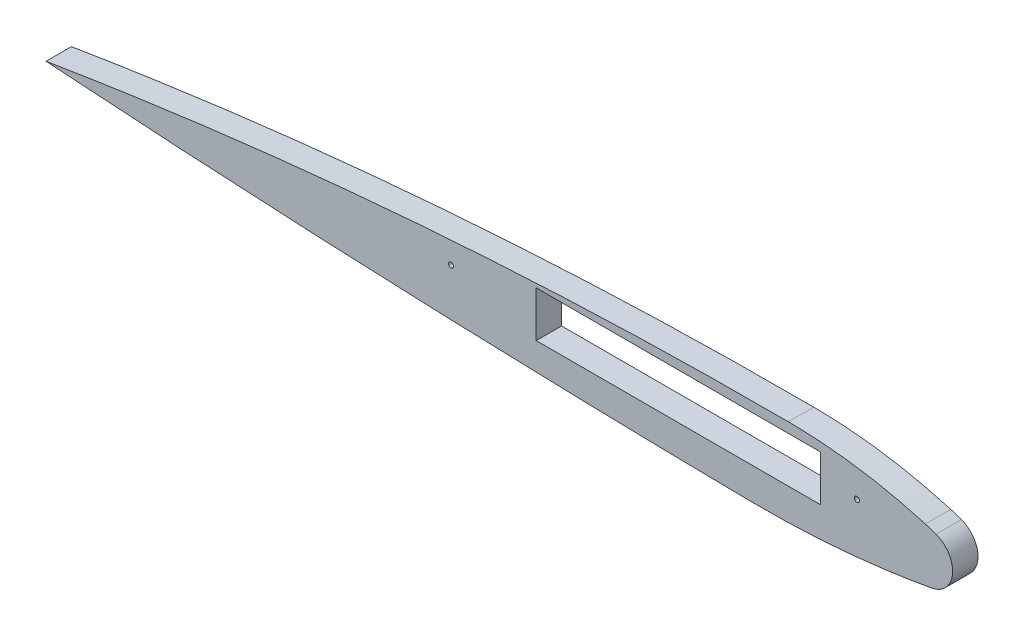
SolidWorks part; units mm, degrees
material "Carbon/Foam Panel"
ref_plane "Front Plane" through (0, 0, 0) normal (0, 0, 1) x (1, 0, 0)
ref_plane "Top Plane" through (0, 0, 0) normal (0, 1, 0) x (1, 0, 0)
ref_plane "Right Plane" through (0, 0, 0) normal (1, 0, 0) x (0, 0, -1)
sketch "Sketch1" plane through (0, 0, 0) normal (0, 0, 1) x (1, 0, 0)
  ellipse E1 centre (30.4917, -1212.2061) end of major axis (1372.9244, -1212.2061) minor radius 1244.6819 (36.9797, 32.4612) -> (-204.2943, 13.2914) ccw
  ellipse E3 centre (36.2563, -106.312) end of major axis (185.9298, -106.312) minor radius 138.7748 (81.5372, 25.9598) -> (36.9797, 32.4612) ccw
  ellipse E5 centre (65.7891, -20.0426) end of major axis (117.8436, -20.0426) minor radius 48.2641 (103.4339, 13.2914) -> (81.5372, 25.9598) ccw
  ellipse E7 centre (28.1769, 268.4704) end of major axis (313.5001, 268.4704) minor radius 264.5471 (24.2792, 3.948) -> (103.4339, 13.2914) ccw
  ellipse E9 centre (66.1797, 2847.5869) end of major axis (3464.1974, 2820.9695) minor radius 2843.9273 (-204.2943, 13.2914) -> (24.2792, 3.948) ccw
extrude "Boss-Extrude1" add sketch "Sketch1" along normal blind 6.35 contours E1 E9 E7 E5 E3
fillet "Fillet1" radius 6.35 1 edges at (103.4339, 13.2914, 3.175)
sketch "Sketch2" plane through (0, 0, 0) normal (0, 0, -1) x (-1, 0, 0)
  line L0 (46.0477, 25.527) -> (46.0477, 14.097) construction
  line L1 (10.4877, 25.527) -> (81.6077, 25.527)
  line L2 (10.4877, 25.527) -> (10.4877, 14.097)
  line L3 (10.4877, 14.097) -> (81.6077, 14.097)
  line L4 (81.6077, 25.527) -> (81.6077, 14.097)
  line L5 (81.6077, 19.812) -> (10.4877, 19.812) construction
  line L6 (13.0277, 25.527) -> (13.0277, 14.097) construction
  line L7 (3.4925, 0) -> (-3.4925, 0) construction
  dimension "D1" = 2.54
  dimension "D2" = 11.43
  dimension "D3" = 68.58
  dimension "D5" = 19.812
extrude "Cut-Extrude1" cut sketch "Sketch2" against normal through all
sketch "Sketch3" plane through (0, 0, 0) normal (0, 0, 1) x (1, 0, 0)
  line L0 (-10.4877, 25.527) -> (-10.4877, 14.097) construction
  line L2 (-102.9437, 19.812) -> (-1.3437, 19.812) construction
  circle A0 centre (-1.3437, 19.812) radius 0.635
  circle A1 centre (-102.9437, 19.812) radius 0.635
  point P7 (-10.4877, 19.812)
  dimension "D1" = 1.27
  dimension "D4" = 1.27
  dimension "D2" = 9.144
  dimension "D3" = 101.6
extrude "Cut-Extrude2" cut sketch "Sketch3" along normal through all
sketch "Sketch6" plane through (0, 0, 0) normal (0, 0, 1) x (1, 0, 0)
  ellipse E1 centre (-23.5091, -930.3417) end of major axis (1010.1641, -930.3417) minor radius 958.4051 (-18.5133, 28.0522) -> (-204.2943, 13.2914) ccw
  ellipse E3 centre (-19.0703, -78.8032) end of major axis (96.1783, -78.8032) minor radius 106.8566 (15.7959, 23.0461) -> (-18.5133, 28.0522) ccw
  ellipse E5 centre (3.6699, -12.3758) end of major axis (43.7519, -12.3758) minor radius 37.1633 (32.6564, 13.2914) -> (15.7959, 23.0461) ccw
  ellipse E7 centre (-25.2915, 209.7792) end of major axis (194.4074, 209.7792) minor radius 203.7012 (-28.2927, 6.097) -> (32.6564, 13.2914) ccw
  ellipse E9 centre (3.9707, 2195.6989) end of major axis (-2612.5029, 2216.1943) minor radius 2189.824 (-204.2943, 13.2914) -> (-28.2927, 6.097) ccw
extrude "Cut-Extrude4" cut sketch "Sketch6" along normal through all flip side to cut
fillet "Fillet3" radius 6.35 1 edges at (32.6564, 13.2914, 3.175)
equation "\"D4@Sketch3\"=\"D1@Sketch3\""
